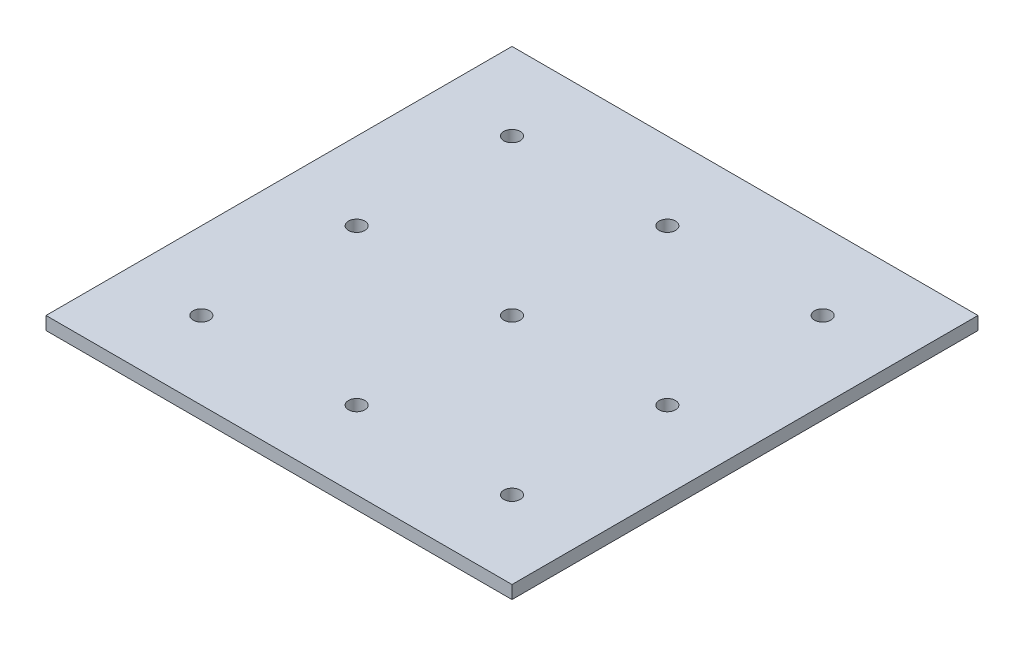
SolidWorks part; units mm, degrees
ref_plane "Front Plane" through (0, 0, 0) normal (0, 0, 1) x (1, 0, 0)
ref_plane "Top Plane" through (0, 0, 0) normal (0, 1, 0) x (1, 0, 0)
ref_plane "Right Plane" through (0, 0, 0) normal (1, 0, 0) x (0, 0, -1)
sketch "Sketch1" plane through (0, 0, 0) normal (0, 1, 0) x (1, 0, 0)
  line L0 (-19, 0) -> (-19, 19) construction
  line L1 (28.5, -28.5) -> (-28.5, -28.5)
  line L2 (28.5, -28.5) -> (28.5, 28.5)
  line L3 (28.5, 28.5) -> (-28.5, 28.5)
  line L4 (-28.5, -28.5) -> (-28.5, 28.5)
  line L5 (28.5, -28.5) -> (-28.5, 28.5) construction
  line L6 (28.5, 28.5) -> (-28.5, -28.5) construction
  line L7 (-19, 0) -> (-19, -19) construction
  circle A0 centre (0, 0) radius 1
  circle A1 centre (-19, 0) radius 1
  circle A2 centre (19, 0) radius 1
  circle A3 centre (-19, 19) radius 1
  circle A4 centre (19, 19) radius 1
  circle A5 centre (0, 19) radius 1
  circle A6 centre (-19, 0) radius 1
  circle A7 centre (19, 0) radius 1
  circle A8 centre (0, 0) radius 1
  circle A9 centre (-19, -19) radius 1
  circle A10 centre (19, -19) radius 1
  circle A11 centre (0, -19) radius 1
  point P0 (0, 0)
  dimension "D2" = 2
  dimension "D1" = 57
  dimension "D3" = 19
  dimension "D4" = 19
  dimension "D7" = 19
  dimension "D8" = 19
  dimension "D5" = 2
  dimension "D6" = 2
extrude "Boss-Extrude1" add sketch "Sketch1" along normal blind 1.6 contours L4 L1 L2 L3 A11 A10 A9 A5 A4 A3 A2 A1 A0
equation "\"D4@Sketch1\"=\"D3@Sketch1\""
